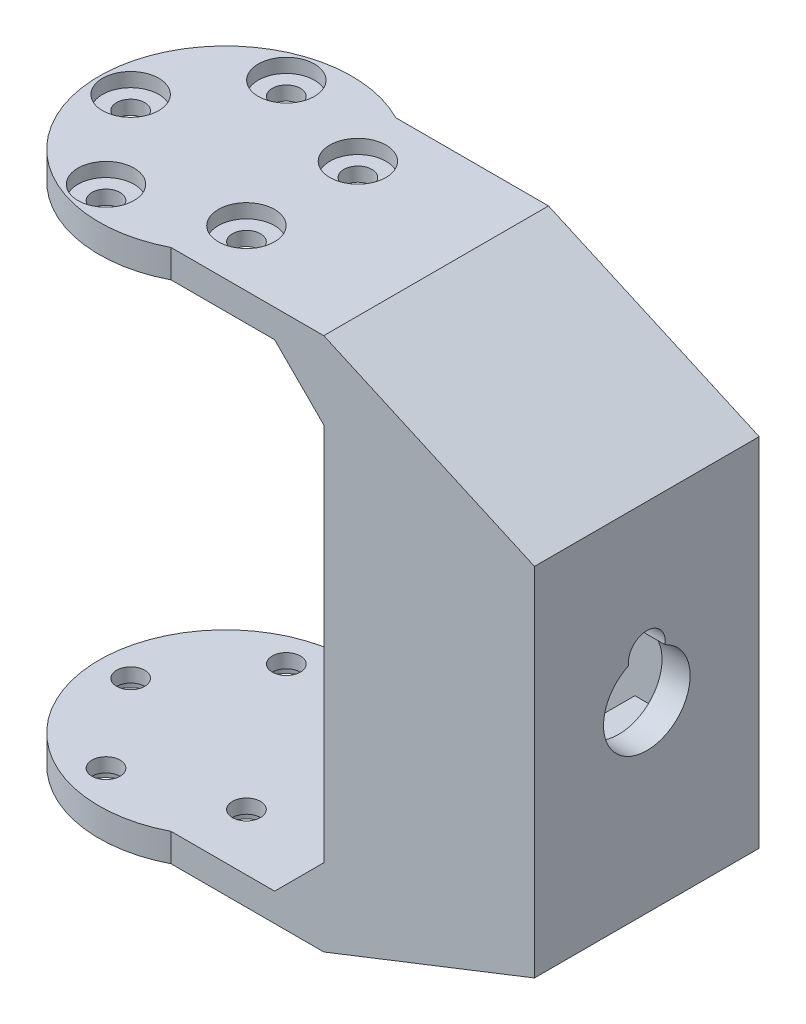
SolidWorks part; units mm, degrees
ref_plane "Front Plane" through (0, 0, 0) normal (0, 0, 1) x (1, 0, 0)
ref_plane "Top Plane" through (0, 0, 0) normal (0, 1, 0) x (1, 0, 0)
ref_plane "Right Plane" through (0, 0, 0) normal (1, 0, 0) x (0, 0, -1)
sketch "Sketch1" plane through (0, 0, 0) normal (0, 1, 0) x (1, 0, 0)
  line L1 (0, 16) -> (60, 16)
  line L2 (0, -16) -> (60, -16)
  line L3 (60, 16) -> (60, -16)
  arc A0 (0, 16) -> (0, -16) centre (0, 0) ccw
  point P3 (19.1549, 0)
  dimension "D1" = 32
  dimension "D2" = 60
extrude "Boss-Extrude1" add sketch "Sketch1" along normal blind 4
sketch "Sketch2" plane through (0, 4, 0) normal (0, 1, 0) x (1, 0, 0)
  line L0 (0, -16) -> (60, -16) construction
  line L1 (60, 16) -> (56, 16)
  line L2 (60, 16) -> (60, -16)
  line L3 (60, -16) -> (56, -16)
  line L4 (56, 16) -> (56, -16)
  dimension "D1" = 4
extrude "Boss-Extrude2" add sketch "Sketch2" along normal blind 72
ref_plane "Plane1" through (0, 38, 0) normal (0, -1, 0) x (-1, 0, 0)
mirror "Mirror1" about plane through (0, 38, 0) normal (0, -1, 0) of "Boss-Extrude1"
sketch "Sketch3" plane through (60, 0, 0) normal (1, 0, 0) x (0, 0, -1)
  line L0 (0, 76) -> (0, 46.6258) construction
  line L1 (-16, 76) -> (16, 76) construction
  line L2 (-16, 38) -> (-6.1698, 38) construction
  line L3 (-16, 76) -> (-16, 0) construction
  line L4 (16, 76) -> (16, 0) construction
  line L5 (0, 31.8302) -> (0, 0) construction
  line L6 (6.1698, 38) -> (16, 38) construction
  arc A1 (-2.5948, 43.5976) -> (2.5948, 43.5976) centre (0, 38) ccw
  arc A2 (2.5948, 43.5976) -> (-2.5948, 43.5976) centre (0, 44) ccw
extrude "Cut-Extrude1" cut sketch "Sketch3" against normal through all
sketch "Sketch4" plane through (56, 0, 0) normal (-1, 0, 0) x (0, 0, 1)
  line L0 (6.3, 59.55) -> (6.3, 55) construction
  line L1 (-6.3, 59.55) -> (6.3, 59.55)
  line L2 (-6.3, 59.55) -> (-6.3, 55.55)
  line L3 (-6.3, 55.55) -> (6.3, 55.55)
  line L4 (6.3, 59.55) -> (6.3, 55.55)
  line L5 (6.3, 32) -> (6.3002, 27.45) construction
  line L6 (-6.2998, 27.45) -> (6.3, 27.45)
  line L7 (-6.2998, 27.45) -> (-6.2998, 31.45)
  line L8 (-6.2998, 31.45) -> (6.3, 31.45)
  line L9 (6.3, 27.45) -> (6.3, 31.45)
  dimension "D1" = 4
  dimension "D2" = 4
extrude "Boss-Extrude3" add sketch "Sketch4" along normal blind 4
sketch "Sketch5" plane through (52, 0, 0) normal (-1, 0, 0) x (0, 0, 1)
  circle A0 centre (0, 57.275) radius 1
  circle A1 centre (0.0151, 29.7329) radius 1
  dimension "D1" = 2
  dimension "D2" = 2
extrude "Cut-Extrude2" cut sketch "Sketch5" against normal blind 4 draft 1
sketch "Sketch10" plane through (0, 76, 0) normal (0, 1, 0) x (1, 0, 0)
  line L0 (30, 16) -> (30, -16) construction
  line L1 (60, 16) -> (0, 16) construction
  line L2 (0, -16) -> (60, -16) construction
sketch "Sketch11" plane through (0, 0, 16) normal (0, 0, 1) x (1, 0, 0)
  line L0 (30, 76) -> (30, 0) construction
  line L1 (0, 76) -> (60, 76) construction
  line L2 (0, 0) -> (60, 0) construction
  line L3 (56, 59.55) -> (30, 72)
  line L4 (0, 72) -> (56, 72) construction
  line L5 (30, 72) -> (30, 76)
  line L6 (30, 76) -> (60, 76)
  line L7 (60, 76) -> (60, 59.55)
  line L8 (60, 76) -> (60, 0) construction
  line L9 (60, 59.55) -> (56, 59.55)
  line L10 (60, 0) -> (60, 14.79)
  line L11 (30, 0) -> (30, 4)
  line L12 (0, 4) -> (56, 4) construction
  line L13 (30, 4) -> (56, 14.79)
  line L14 (30, 0) -> (60, 0)
  line L15 (56, 14.79) -> (60, 14.79)
  line L16 (56, 72) -> (56, 4) construction
  dimension "D1" = 16.45
extrude "Cut-Extrude4" cut sketch "Sketch11" against normal through all
sketch "Sketch12" plane through (0, 0, 16) normal (0, 0, 1) x (1, 0, 0)
  line L0 (30, 72) -> (56, 59.55)
  line L1 (56, 59.55) -> (60, 59.55)
  line L3 (30, 76) -> (30, 72)
  line L4 (30, 4) -> (56, 14.79)
  line L5 (56, 14.79) -> (60, 14.79)
  line L7 (30, 0) -> (30, 4)
  line L8 (60, 59.55) -> (60, 62.55)
  line L9 (60, 14.79) -> (60, 11.79)
  line L10 (30, 76) -> (60, 62.55)
  line L11 (30, 0) -> (60, 11.79)
  dimension "D1" = 3
  dimension "D2" = 3
extrude "Boss-Extrude6" add sketch "Sketch12" against normal through all
sketch "Sketch13" plane through (0, 0, 16) normal (0, 0, 1) x (1, 0, 0)
  line L0 (30, 76) -> (30, 0)
  line L1 (30, 0) -> (60, 11.79) construction
  line L2 (30, 0) -> (60, 11.79)
  line L3 (60, 11.79) -> (60, 62.55)
  line L4 (60, 62.55) -> (30, 76)
extrude "Boss-Extrude7" add sketch "Sketch13" against normal blind 2
ref_plane "Plane2" through (0, 0, 0) normal (0, 0, 1) x (1, 0, 0)
mirror "Mirror2" about plane through (0, 0, 0) normal (0, 0, 1) of "Boss-Extrude7"
sketch "Sketch14" plane through (0, 76, 0) normal (0, 1, 0) x (1, 0, 0)
  circle A0 centre (0, 0) radius 16
  circle A1 centre (0, 0) radius 18
  dimension "D1" = 2
extrude "Boss-Extrude8" add sketch "Sketch14" against normal blind 4
sketch "Sketch15" plane through (0, 76, 0) normal (0, 1, 0) x (1, 0, 0)
  circle A3 centre (-13.5, 0) radius 2
  circle A4 centre (-4.1717, 12.8393) radius 2
  circle A5 centre (10.9217, 7.9351) radius 2
  circle A6 centre (10.9217, -7.9351) radius 2
  circle A7 centre (-4.1717, -12.8393) radius 2
  point P18 (0, 0)
  dimension "D3" = 4
  dimension "D4" = 5
extrude "Cut-Extrude5" cut sketch "Sketch15" against normal blind 4
mirror "Mirror3" about plane through (0, 38, 0) normal (0, -1, 0) of "Cut-Extrude5", "Boss-Extrude8"
sketch "Sketch16" plane through (0, 0, 0) normal (0, -1, 0) x (1, 0, 0)
  circle A1 centre (-4.1717, 12.8393) radius 2
  circle A2 centre (-4.1717, 12.8393) radius 4
  circle A3 centre (10.9217, 7.9351) radius 4
  circle A4 centre (10.9217, 7.9351) radius 2
  circle A5 centre (10.9217, -7.9351) radius 4
  circle A6 centre (10.9217, -7.9351) radius 2
  circle A7 centre (-4.1717, -12.8393) radius 4
  circle A8 centre (-4.1717, -12.8393) radius 2
  circle A9 centre (-13.5, 0) radius 4
  circle A10 centre (-13.5, 0) radius 2
  point P22 (0, 0)
  dimension "D1" = 2
  dimension "D2" = 5
extrude "Cut-Extrude6" cut sketch "Sketch16" against normal blind 2
mirror "Mirror4" about plane through (0, 38, 0) normal (0, -1, 0) of "Cut-Extrude6"
sketch "Sketch17" plane through (0, 0, -16) normal (0, 0, -1) x (-1, 0, 0)
  line L0 (-30, 72) -> (-30, 4) construction
  line L1 (-47.5, 43) -> (-42.5, 43)
  line L2 (-47.5, 43) -> (-47.5, 33)
  line L3 (-47.5, 33) -> (-42.5, 33)
  line L4 (-42.5, 43) -> (-42.5, 33)
  line L5 (-60, 62.55) -> (-30, 62.55) construction
  point P11 (-45, 43)
  point P12 (-45, 62.55)
  point P13 (-30, 38)
  point P14 (-42.5, 38)
  dimension "D1" = 10
  dimension "D2" = 5
extrude "Cut-Extrude7" cut sketch "Sketch17" against normal blind 10
sketch "Sketch18" plane through (0, 0, -16) normal (0, 0, -1) x (-1, 0, 0)
  line L0 (-30, 11) -> (-27, 8)
  line L5 (-30, 72) -> (-30, 4) construction
  line L6 (-30, 4) -> (-8.2462, 4) construction
  line L7 (-26, 7) -> (-23, 4)
  line L8 (-30, 11) -> (-30, 4)
  line L9 (-30, 4) -> (-23, 4)
  line L10 (-27, 8) -> (-26, 7)
extrude "Boss-Extrude9" add sketch "Sketch18" against normal blind 2
mirror "Mirror5" about plane through (0, 0, 0) normal (0, 0, 1) of "Boss-Extrude9"
mirror "Mirror6" about plane through (0, 38, 0) normal (0, -1, 0) of "Boss-Extrude9", "Mirror5"
fillet "Fillet1" radius 10 1 edges at (30, 72, 0)
fillet "Fillet2" radius 10 1 edges at (30, 4, 0)
